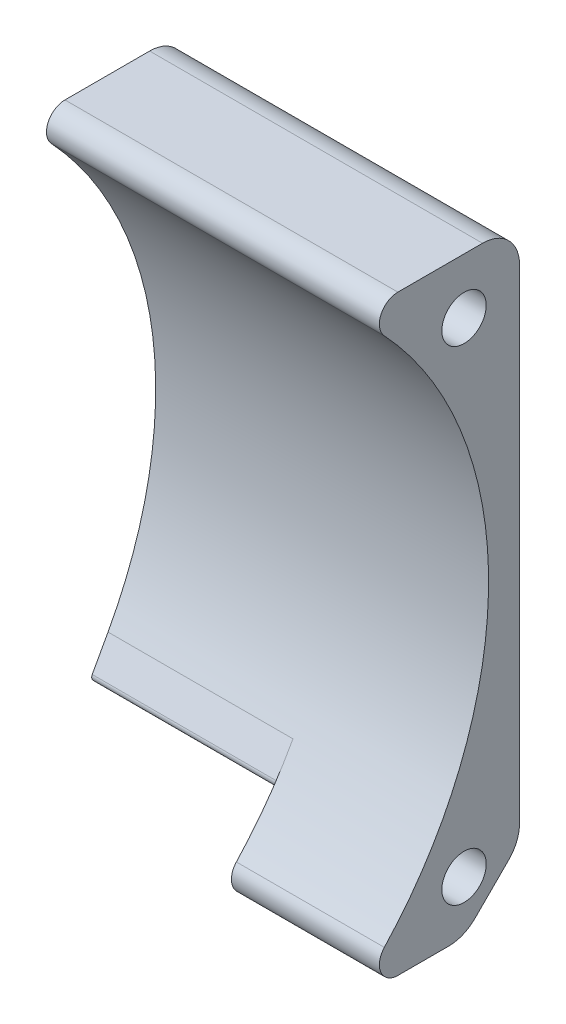
SolidWorks part; units mm, degrees
ref_plane "Front Plane" through (0, 0, 0) normal (0, 0, 1) x (1, 0, 0)
ref_plane "Top Plane" through (0, 0, 0) normal (0, 1, 0) x (1, 0, 0)
ref_plane "Right Plane" through (0, 0, 0) normal (1, 0, 0) x (0, 0, -1)
sketch "Sketch1" plane through (0, 0, 0) normal (1, 0, 0) x (0, 0, -1)
  line L0 (0, 0) -> (-14.3998, 0)
  line L1 (0, 0) -> (0, -50.8)
  line L3 (-3.175, 0) -> (-35.8474, 0) construction
  line L10 (-14.3998, -50.8) -> (0, -50.8)
  line L11 (-362.2224, -50.8) -> (-6.0776, -50.8) construction
  arc A0 (-14.3998, 0) -> (-14.3998, -50.8) centre (-35.9921, -25.4) cw
  arc A1 (-356.695, -2.6699) -> (-356.695, -48.1301) centre (-332.3079, -25.4) ccw construction
extrude "Boss-Extrude1" add sketch "Sketch1" along normal blind 28.575
chamfer "Chamfer1" distance 4.7625 angle 45 1 edges at (14.2875, -50.8, 0)
fillet "Fillet3" radius 3.175 2 edges at (14.2875, -50.8, 4.7625) (14.2875, -46.0375, 0)
sketch "Sketch2" plane through (28.575, 0, 0) normal (1, 0, 0) x (0, 0, -1)
  line L4 (-9.4322, -46.3099) -> (-6.748, -41.4053)
  line L5 (-14.3998, -50.8) -> (-6.0776, -50.8) construction
  line L6 (-14.3998, -50.8) -> (-6.0776, -50.8)
  line L7 (-3.8326, -49.8701) -> (-0.9299, -46.9674) construction
  line L8 (-0.0928, -46.3099) -> (-4.7625, -41.6401)
  line L9 (-4.7625, -50.9796) -> (-0.0928, -46.3099)
  line L10 (-9.4322, -46.3099) -> (-4.7625, -50.9796)
  line L11 (-4.7625, -41.6401) -> (-9.4322, -46.3099)
  line L12 (-0.3106, -46.092) -> (-4.7625, -41.6401)
  line L15 (-4.7625, -41.6401) -> (-9.4322, -46.3099)
  line L16 (-3.8326, -49.8701) -> (-0.9299, -46.9674)
  arc A0 (-14.3998, -50.8) -> (-14.3998, 0) centre (-35.9921, -25.4) ccw construction
  arc A1 (-14.3998, -50.8) -> (-6.748, -41.4053) centre (-35.9921, -25.4) ccw
  arc A2 (-6.0776, -50.8) -> (-3.8326, -49.8701) centre (-6.0776, -47.625) ccw construction
  arc A3 (-6.0776, -50.8) -> (-3.8326, -49.8701) centre (-6.0776, -47.625) ccw
  arc A4 (-0.9299, -46.9674) -> (0, -44.7224) centre (-3.175, -44.7224) ccw construction
  arc A5 (-0.9299, -46.9674) -> (-0.3106, -46.092) centre (-3.175, -44.7224) ccw
  dimension "D1" = 0.127
extrude "Cut-Extrude1" cut sketch "Sketch2" against normal through all from offset 12.7 offset against normal yes
fillet "Fillet4" radius 0.3969 1 edges at (7.9375, -46.3099, 9.4322)
fillet "Fillet5" radius 3.175 1 edges at (14.2875, 0, 0)
fillet "Fillet6" radius 1.5875 2 edges at (22.225, -50.8, 14.3998) (14.2875, 0, 14.3998)
sketch "Sketch3" plane through (28.575, 0, 0) normal (1, 0, 0) x (0, 0, -1)
  line L0 (-3.175, 0) -> (-10.4437, 0) construction
  line L1 (0, -44.7224) -> (0, -3.175) construction
  circle A0 centre (-4.7625, -4.7625) radius 4.7625 construction
  circle A1 centre (-4.7625, -4.7625) radius 1.905
  circle A2 centre (-4.7625, -46.3099) radius 1.905
  circle A3 centre (-4.7625, -46.3099) radius 1.651 construction
  dimension "D1" = 9.525
  dimension "D2" = 3.81
  dimension "D3" = 3.81
extrude "Cut-Extrude2" cut sketch "Sketch3" against normal through all
